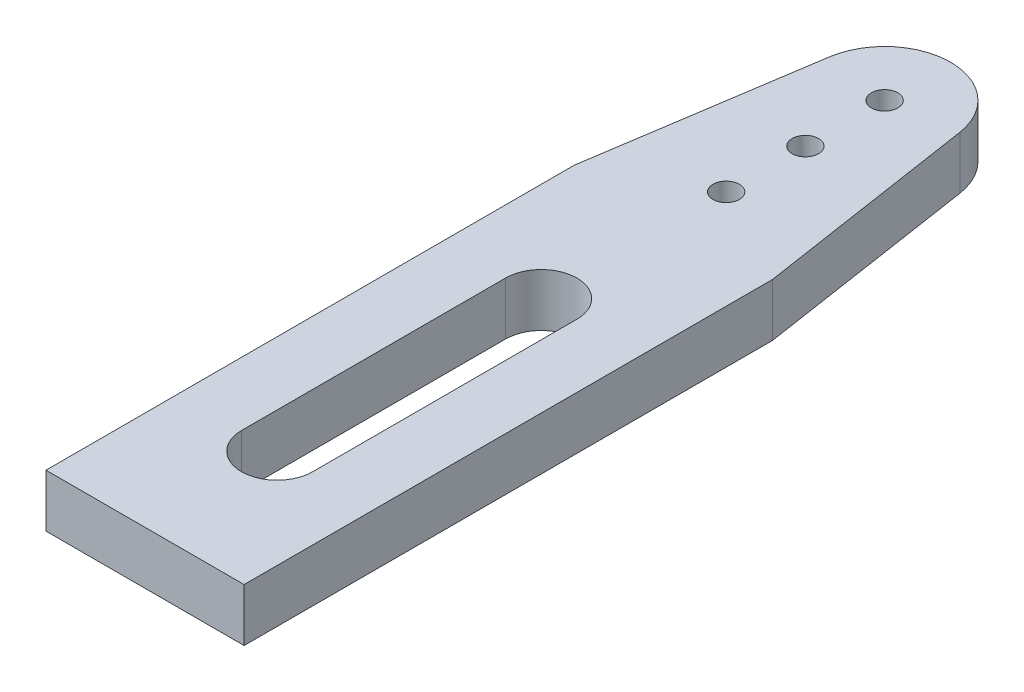
SolidWorks part; units mm, degrees
material "PE haute densité"
ref_plane "Plan de face" through (0, 0, 0) normal (0, 0, 1) x (1, 0, 0)
ref_plane "Plan de dessus" through (0, 0, 0) normal (0, 1, 0) x (1, 0, 0)
ref_plane "Plan de droite" through (0, 0, 0) normal (1, 0, 0) x (0, 0, -1)
sketch "Esquisse1" plane through (0, 0, 0) normal (0, 1, 0) x (1, 0, 0)
  line L0 (0, 0) -> (0, 10) construction
  line L1 (-1.35, 0) -> (-1.35, 10)
  line L2 (1.35, 0) -> (1.35, 10)
  line L3 (-3.75, 15) -> (-2.4714, 23.3772)
  line L4 (-3.75, -5) -> (3.75, -5)
  line L5 (-3.75, -5) -> (-3.75, 15)
  line L6 (-3.75, 15) -> (3.75, 15) construction
  line L7 (3.75, -5) -> (3.75, 15)
  line L8 (2.4714, 23.3772) -> (3.75, 15)
  arc A0 (-1.35, 0) -> (1.35, 0) centre (0, 0) ccw
  arc A1 (1.35, 10) -> (-1.35, 10) centre (0, 10) ccw
  arc A2 (-2.4714, 23.3772) -> (2.4714, 23.3772) centre (0, 23) cw
  circle A3 centre (0, 23) radius 0.5
  circle A4 centre (0, 20) radius 0.5
  circle A5 centre (0, 17) radius 0.5
  point P3 (0, 5)
  point P16 (0, -5)
  dimension "D1" = 2.7
  dimension "D2" = 7.5
  dimension "D3" = 5
  dimension "D4" = 1.35
  dimension "D6" = 2.5
  dimension "D7" = 28
  dimension "D9" = 1
  dimension "D10" = 3
  dimension "D11" = 3
  dimension "D5" = 20
  dimension "D8" = 10
extrude "Boss.-Extru.4" add sketch "Esquisse1" along normal blind 2
